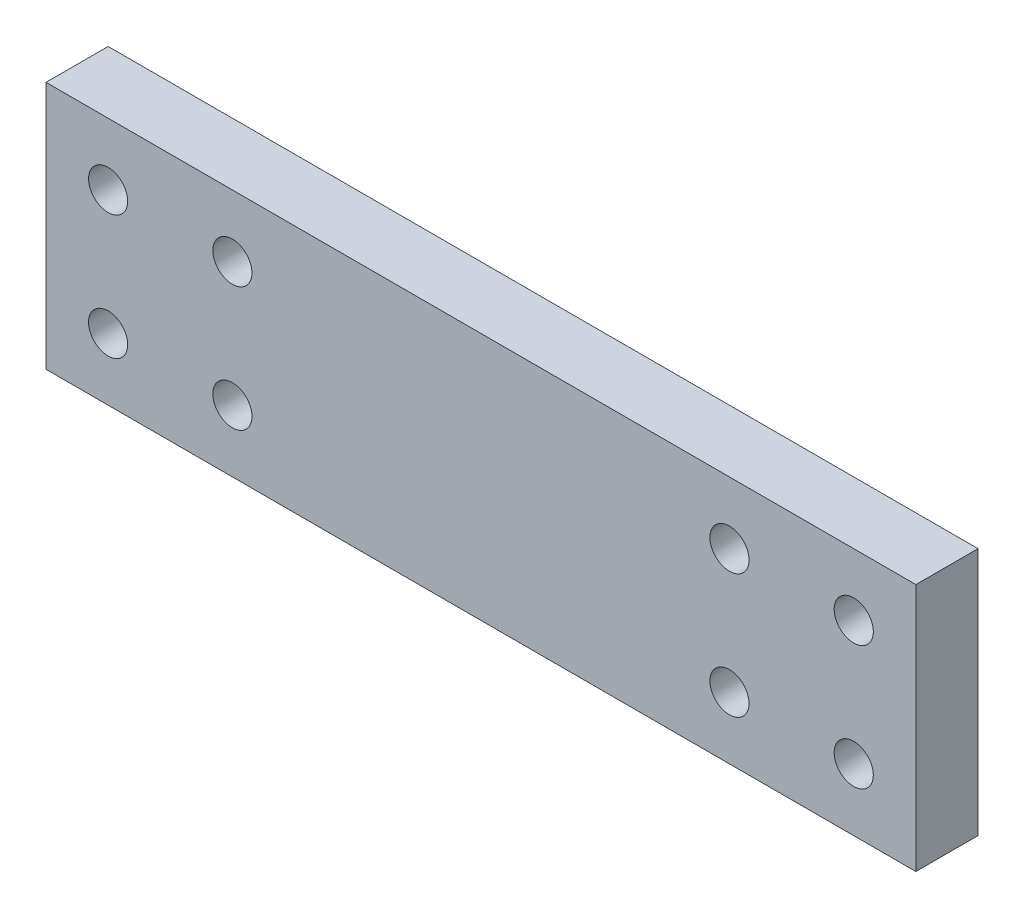
SolidWorks part; units mm, degrees
ref_plane "前视基准面" through (0, 0, 0) normal (0, 0, 1) x (1, 0, 0)
ref_plane "上视基准面" through (0, 0, 0) normal (0, 1, 0) x (1, 0, 0)
ref_plane "右视基准面" through (0, 0, 0) normal (1, 0, 0) x (0, 0, -1)
other "Configuration Table"
sketch "草图1" plane through (0, 0, 0) normal (0, 0, 1) x (1, 0, 0)
  line L1 (0, 0) -> (70, 0)
  line L2 (0, 0) -> (0, -20)
  line L3 (0, -20) -> (70, -20)
  line L4 (70, 0) -> (70, -20)
  dimension "D1" = 70
  dimension "D2" = 20
extrude "凸台-拉伸1" add sketch "草图1" along normal blind 5
sketch "草图2" plane through (0, 0, 5) normal (0, 0, 1) x (1, 0, 0)
  line L0 (35, 0) -> (35, -20) construction
  line L1 (70, 0) -> (0, 0) construction
  line L2 (0, -20) -> (70, -20) construction
  line L3 (10, 0) -> (10, -20) construction
  line L4 (0, -10) -> (10, -10) construction
  line L5 (0, 0) -> (0, -20) construction
  line L6 (70, -10) -> (60, -10) construction
  line L7 (60, 0) -> (60, -20) construction
  circle A0 centre (5, -5) radius 1.575
  circle A1 centre (5, -15) radius 1.575
  circle A2 centre (15, -15) radius 1.575
  circle A3 centre (15, -5) radius 1.575
  circle A4 centre (55, -5) radius 1.575
  circle A5 centre (55, -15) radius 1.575
  circle A6 centre (65, -15) radius 1.575
  circle A7 centre (65, -5) radius 1.575
  dimension "D1" = 3.15
  dimension "D2" = 10
  dimension "D3" = 5
  dimension "D4" = 5
extrude "切除-拉伸1" cut sketch "草图2" against normal through all
